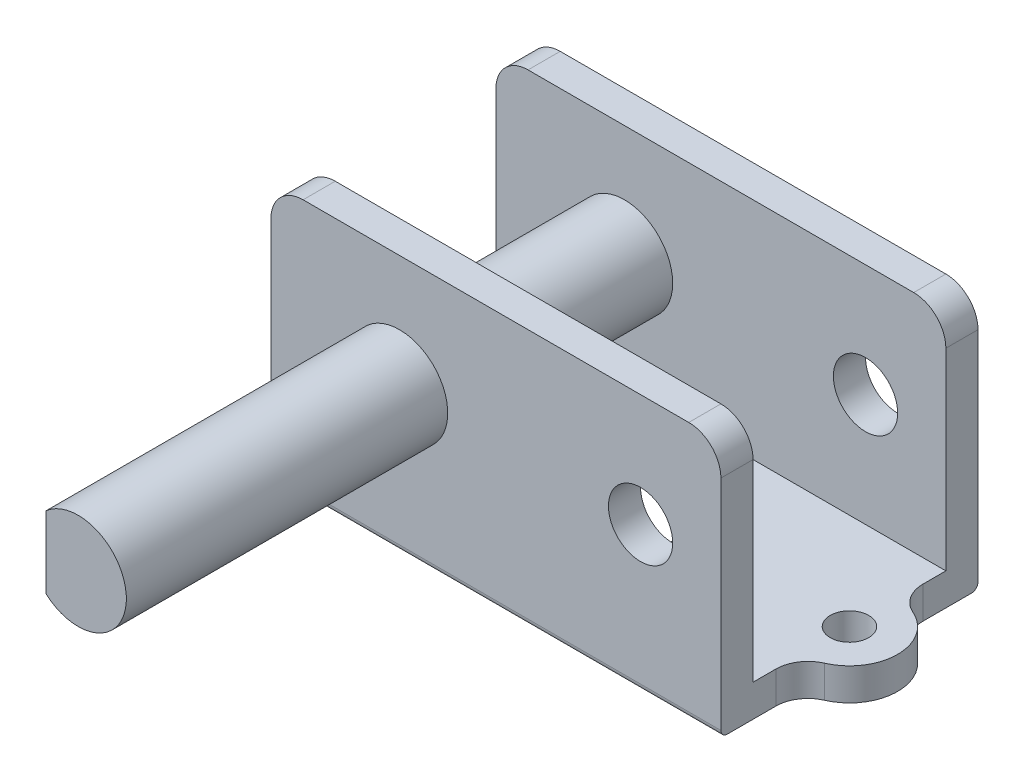
SolidWorks part; units mm, degrees
ref_plane "Спереди" through (0, 0, 0) normal (0, 0, 1) x (1, 0, 0)
ref_plane "Сверху" through (0, 0, 0) normal (0, 1, 0) x (1, 0, 0)
ref_plane "Справа" through (0, 0, 0) normal (1, 0, 0) x (0, 0, -1)
sketch "Sketch1" plane through (0, 0, 0) normal (0, 0, 1) x (1, 0, 0)
  line L0 (0, 0) -> (-7, 0)
  line L1 (-7, 0) -> (-7, 8)
  line L2 (-7, 8) -> (7, 8)
  line L3 (7, 8) -> (7, 0)
  line L4 (7, 0) -> (0, 0)
extrude "Extrude1" add sketch "Sketch1" along normal mid plane 8
sketch "Sketch2" plane through (0, 0, 0) normal (0, 0, 1) x (1, 0, 0)
  line L0 (7, 8) -> (7, 4.5) construction
  line L1 (7, 4.5) -> (4.5, 4.5) construction
  circle A0 centre (4.5, 4.5) radius 1
extrude "Extrude2" cut sketch "Sketch2" against normal through all both and the other way through all
sketch "Sketch3" plane through (0, 0, 0) normal (0, 0, 1) x (1, 0, 0)
  line L0 (-7, 8) -> (-3, 8)
  line L1 (-3, 8) -> (-3, 4.5)
  circle A0 centre (-3, 4.5) radius 1.5
sketch "Sketch4" plane through (0, 0, 0) normal (1, 0, 0) x (0, 0, -1)
  line L0 (0, 0) -> (0, 1)
  line L1 (3, 1) -> (-3, 1)
  line L2 (-3, 1) -> (-3, 9.732)
  line L3 (3, 1) -> (3, 9.732)
  line L4 (-3, 9.732) -> (3, 9.732)
extrude "Extrude3" cut sketch "Sketch4" against normal through all both and the other way through all contours L4 L2 L1 L3
fillet "Fillet1" radius 0.2 2 edges at (0, 0, 4) (0, 0, -4)
fillet "Fillet2" radius 1 4 edges at (7, 8, -3.5) (7, 8, 3.5) (-7, 8, -3.5) (-7, 8, 3.5)
extrude "Extrude4" add sketch "Sketch3" along normal blind 14 and the other way blind 3
sketch "Sketch5" plane through (0, 0, 14) normal (0, 0, 1) x (1, 0, 0)
  line L0 (-1.5, 4.5) -> (-4, 4.5)
  line L1 (-4, 4.5) -> (-4, 6.0607)
  line L2 (-4, 6.0607) -> (-4.9564, 6.0607)
  line L3 (-4.9564, 6.0607) -> (-4.9564, 2.5)
  line L4 (-4.9564, 2.5) -> (-4, 2.5)
  line L5 (-4, 2.5) -> (-4, 4.5)
  circle A0 centre (-3, 4.5) radius 1.5 construction
  circle A1 centre (-3, 4.5) radius 1.5 construction
  circle M1 centre (-3, 4.5) radius 1.5
extrude "Extrude5" cut sketch "Sketch5" against normal blind 9 contours L4 L5 L1 L2 L3 M1 | L5 L1 M1
sketch "Sketch6" plane through (0, 0, 0) normal (0, -1, 0) x (1, 0, 0)
  line L0 (0, 0) -> (-8.5, 0)
  line L2 (0, 0) -> (0, 5.5899)
  circle A1 centre (-7, 0) radius 1.5
  circle A2 centre (0, 0) radius 6
  circle A3 centre (7, 0) radius 1.5
extrude "Extrude6" add sketch "Sketch6" against normal blind 1
sketch "Sketch7" plane through (0, 0, 0) normal (0, -1, 0) x (1, 0, 0)
  circle A0 centre (-7, 0) radius 0.6
  circle A1 centre (7, 0) radius 0.6
extrude "Extrude7" cut sketch "Sketch7" against normal blind 1
fillet "Fillet3" radius 1 4 edges at (7, 0.5, -1.5) (7, 0.5, 1.5) (-7, 0.5, 1.5) (-7, 0.5, -1.5)
sketch "Sketch8" plane through (0, 0, 0) normal (0, -1, 0) x (1, 0, 0)
  circle A0 centre (0, 0) radius 2
extrude "Extrude8" cut sketch "Sketch8" against normal blind 1
